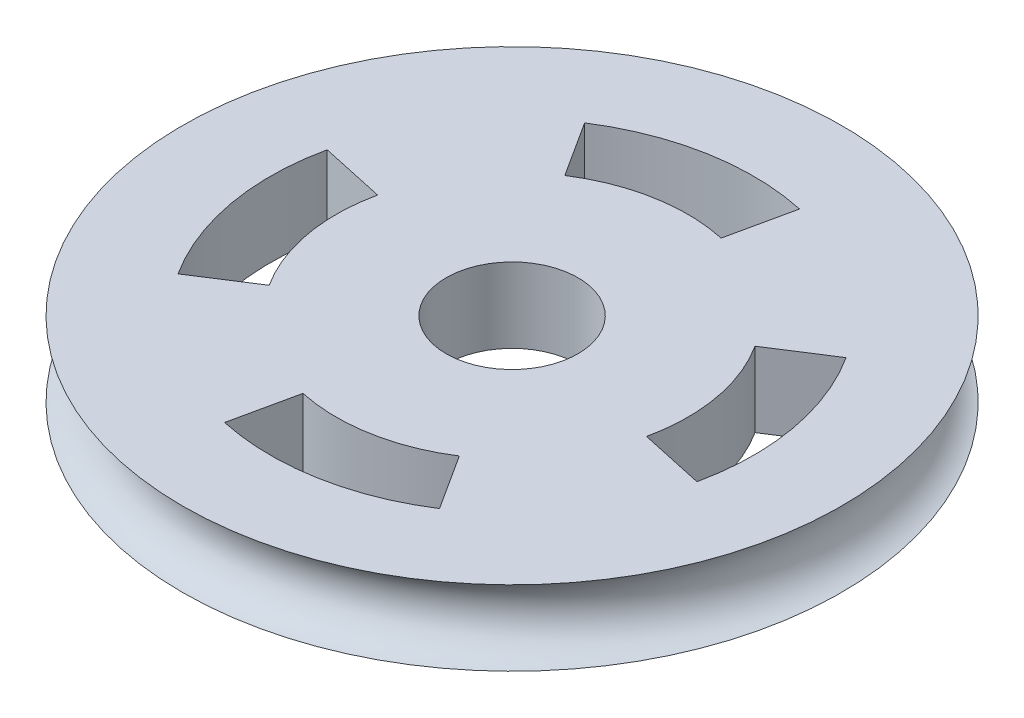
SolidWorks part; units mm, degrees
ref_plane "Piano frontale" through (0, 0, 0) normal (0, 0, 1) x (1, 0, 0)
ref_plane "Piano superiore" through (0, 0, 0) normal (0, 1, 0) x (1, 0, 0)
ref_plane "Piano destro" through (0, 0, 0) normal (1, 0, 0) x (0, 0, -1)
sketch "Schizzo1" plane through (0, 0, 0) normal (0, 0, 1) x (1, 0, 0)
  line L1 (7.7, 1.619) -> (7.7, -1.6431) construction
  line L2 (0.2, 0.8518) -> (6.2, 0.8518)
  line L4 (0.2, -0.8518) -> (6.2, -0.8518)
  line L5 (6.2, 0.8518) -> (6.2, -0.8518)
  arc A0 (0.2, -0.8518) -> (0.2, 0.8518) centre (0, 0) ccw
  dimension "D1" = 1.75
  dimension "D3" = 6
  dimension "D4" = 1.5
revolve "Rivoluzione1" add sketch "Schizzo1" angle 360 about L1
sketch "Schizzo2" plane through (0, -0.8518, 0) normal (0, -1, 0) x (1, 0, 0)
  line L2 (3.0742, 2.9752) -> (7.7, 0)
  line L3 (7.7, 0) -> (2.3253, -1.1672)
  arc A0 (3.0742, 2.9752) -> (2.3253, -1.1672) centre (7.7, 0) ccw
  arc A1 (4.3358, 2.1638) -> (3.7911, -0.8489) centre (7.7, 0) ccw
  dimension "D1" = 11
  dimension "D2" = 8
  dimension "D3" = 45
extrude "Taglio-Estrusione1" cut sketch "Schizzo2" against normal through all
pattern_circular "RipetizioneCircolare1" count 4 every 90 about axis through (7.7, -0.8518, 0) along (0, 1, 0) of "Taglio-Estrusione1"
